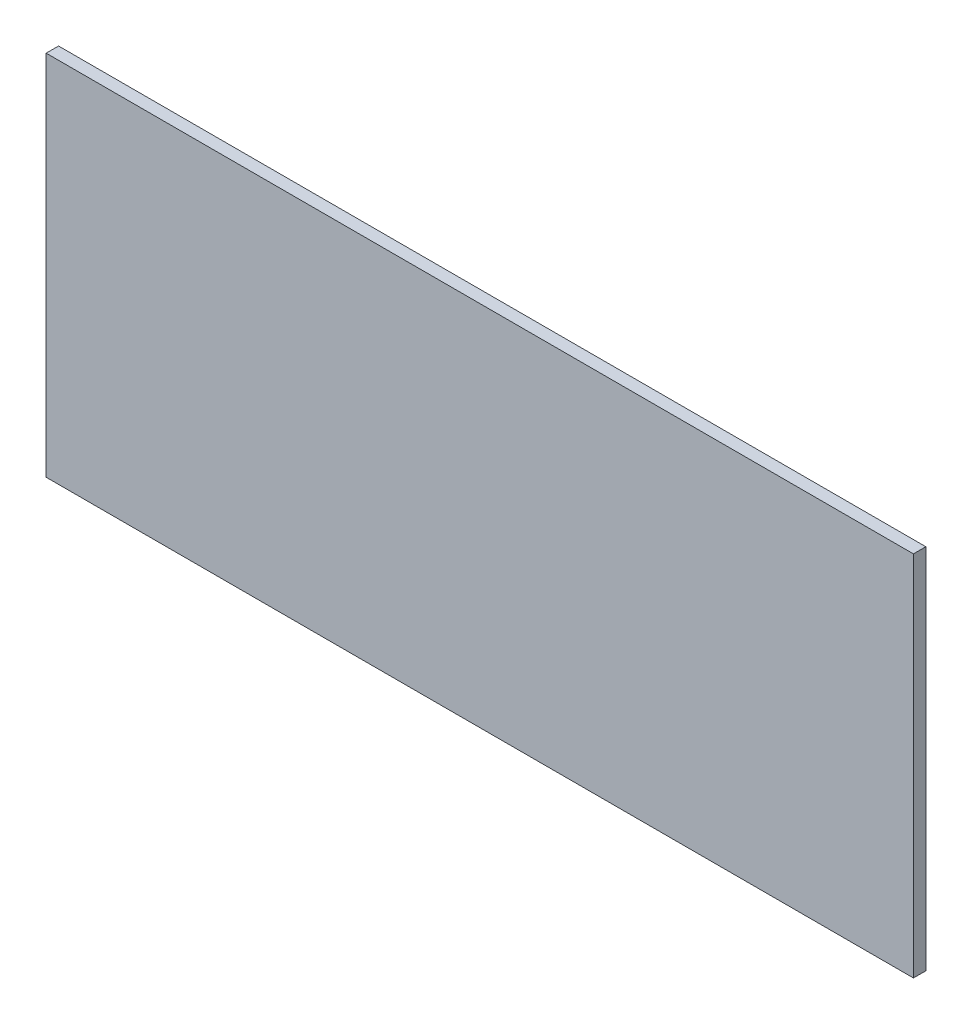
SolidWorks part; units mm, degrees
ref_plane "Front Plane" through (0, 0, 0) normal (0, 0, 1) x (1, 0, 0)
ref_plane "Top Plane" through (0, 0, 0) normal (0, 1, 0) x (1, 0, 0)
ref_plane "Right Plane" through (0, 0, 0) normal (1, 0, 0) x (0, 0, -1)
sketch "Sketch1" plane through (0, 0, 0) normal (0, 0, 1) x (1, 0, 0)
  line L1 (-104.9528, -44.45) -> (104.9528, -44.45)
  line L2 (-104.9528, -44.45) -> (-104.9528, 44.45)
  line L3 (-104.9528, 44.45) -> (104.9528, 44.45)
  line L4 (104.9528, -44.45) -> (104.9528, 44.45)
  line L5 (-104.9528, -44.45) -> (104.9528, 44.45) construction
  line L6 (-104.9528, 44.45) -> (104.9528, -44.45) construction
  point P0 (0, 0)
  dimension "D1" = 209.9056
  dimension "D2" = 88.9
extrude "Boss-Extrude1" add sketch "Sketch1" along normal blind 3
